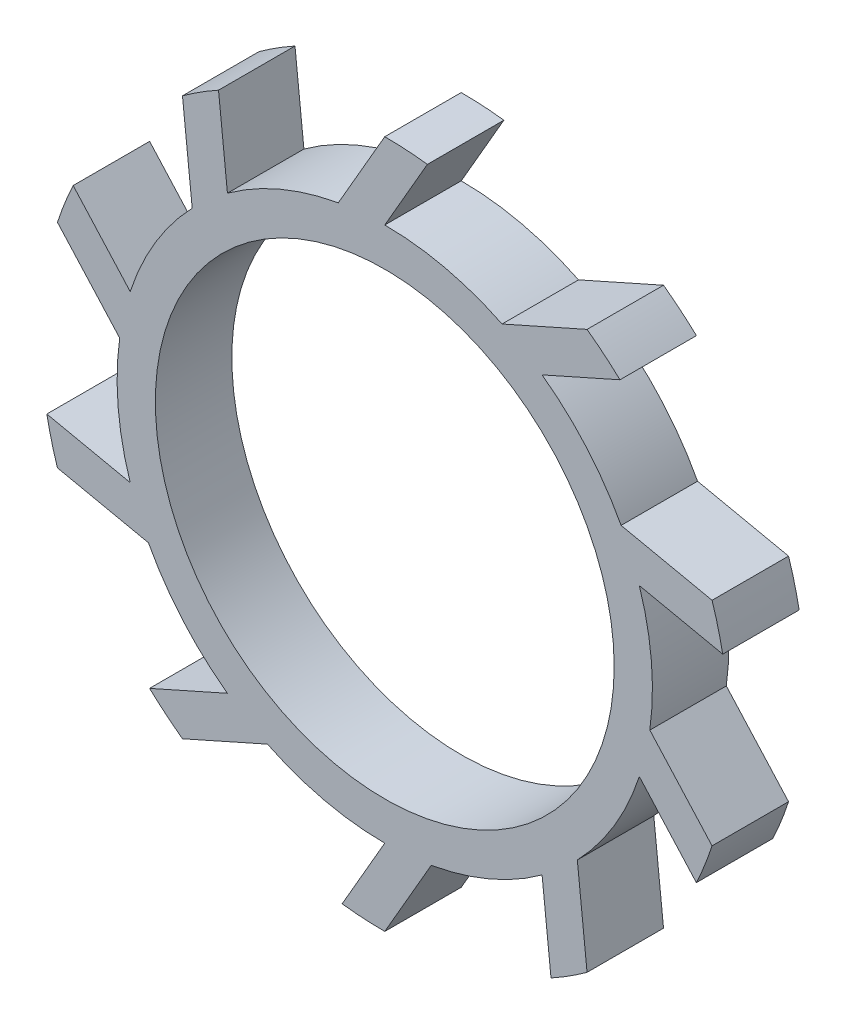
SolidWorks part; units mm, degrees
ref_plane "Front Plane" through (0, 0, 0) normal (0, 0, 1) x (1, 0, 0)
ref_plane "Top Plane" through (0, 0, 0) normal (0, 1, 0) x (1, 0, 0)
ref_plane "Right Plane" through (0, 0, 0) normal (1, 0, 0) x (0, 0, -1)
sketch "Sketch1" plane through (0, 0, 0) normal (0, 0, 1) x (1, 0, 0)
  line L0 (0, -1000) -> (0, 49000) construction
  line L1 (0, 22.5) -> (-3.0404, 17.2339)
  line L2 (0, 17.5) -> (2.7867, 22.3268)
  line L3 (13.2252, 18.2029) -> (7.6701, 15.7296)
  line L4 (10.2862, 14.1578) -> (15.3779, 16.4247)
  line L5 (21.3988, 6.9529) -> (15.4508, 8.2172)
  line L6 (16.6435, 5.4078) -> (22.0952, 4.249)
  line L7 (21.3988, -6.9529) -> (17.3299, -2.434)
  line L8 (16.6435, -5.4078) -> (20.3729, -9.5497)
  line L9 (13.2252, -18.2029) -> (12.5895, -12.1554)
  line L10 (10.2862, -14.1578) -> (10.8688, -19.7007)
  line L11 (0, -22.5) -> (3.0404, -17.2339)
  line L12 (0, -17.5) -> (-2.7867, -22.3268)
  line L13 (-13.2252, -18.2029) -> (-7.6701, -15.7296)
  line L14 (-10.2862, -14.1578) -> (-15.3779, -16.4247)
  line L15 (-21.3988, -6.9529) -> (-15.4508, -8.2172)
  line L16 (-16.6435, -5.4078) -> (-22.0952, -4.249)
  line L17 (-21.3988, 6.9529) -> (-17.3299, 2.434)
  line L18 (-16.6435, 5.4078) -> (-20.3729, 9.5497)
  line L19 (-13.2252, 18.2029) -> (-12.5895, 12.1554)
  line L20 (-10.2862, 14.1578) -> (-10.8688, 19.7007)
  circle A0 centre (0, 0) radius 15
  arc A1 (-3.0404, 17.2339) -> (-10.2862, 14.1578) centre (0, 0) ccw
  arc A2 (-10.8688, 19.7007) -> (-13.2252, 18.2029) centre (0, 0) ccw
  arc A3 (-12.5895, 12.1554) -> (-16.6435, 5.4078) centre (0, 0) ccw
  arc A4 (2.7867, 22.3268) -> (0, 22.5) centre (0, 0) ccw
  arc A5 (7.6701, 15.7296) -> (0, 17.5) centre (0, 0) ccw
  arc A6 (15.3779, 16.4247) -> (13.2252, 18.2029) centre (0, 0) ccw
  arc A7 (15.4508, 8.2172) -> (10.2862, 14.1578) centre (0, 0) ccw
  arc A8 (22.0952, 4.249) -> (21.3988, 6.9529) centre (0, 0) ccw
  arc A9 (17.3299, -2.434) -> (16.6435, 5.4078) centre (0, 0) ccw
  arc A10 (20.3729, -9.5497) -> (21.3988, -6.9529) centre (0, 0) ccw
  arc A11 (12.5895, -12.1554) -> (16.6435, -5.4078) centre (0, 0) ccw
  arc A12 (10.8688, -19.7007) -> (13.2252, -18.2029) centre (0, 0) ccw
  arc A13 (3.0404, -17.2339) -> (10.2862, -14.1578) centre (0, 0) ccw
  arc A14 (-2.7867, -22.3268) -> (0, -22.5) centre (0, 0) ccw
  arc A15 (-7.6701, -15.7296) -> (0, -17.5) centre (0, 0) ccw
  arc A16 (-15.3779, -16.4247) -> (-13.2252, -18.2029) centre (0, 0) ccw
  arc A17 (-15.4508, -8.2172) -> (-10.2862, -14.1578) centre (0, 0) ccw
  arc A18 (-22.0952, -4.249) -> (-21.3988, -6.9529) centre (0, 0) ccw
  arc A19 (-17.3299, 2.434) -> (-16.6435, -5.4078) centre (0, 0) ccw
  arc A20 (-20.3729, 9.5497) -> (-21.3988, 6.9529) centre (0, 0) ccw
  point P50 (0, 0)
  dimension "D1" = 30
  dimension "D2" = 35
  dimension "D3" = 45
  dimension "D4" = 30
  dimension "D5" = 10
extrude "Boss-Extrude1" add sketch "Sketch1" along normal mid plane 5
scale "Scale1" scale about centroid uniform scaling yes scale factor 1.5
